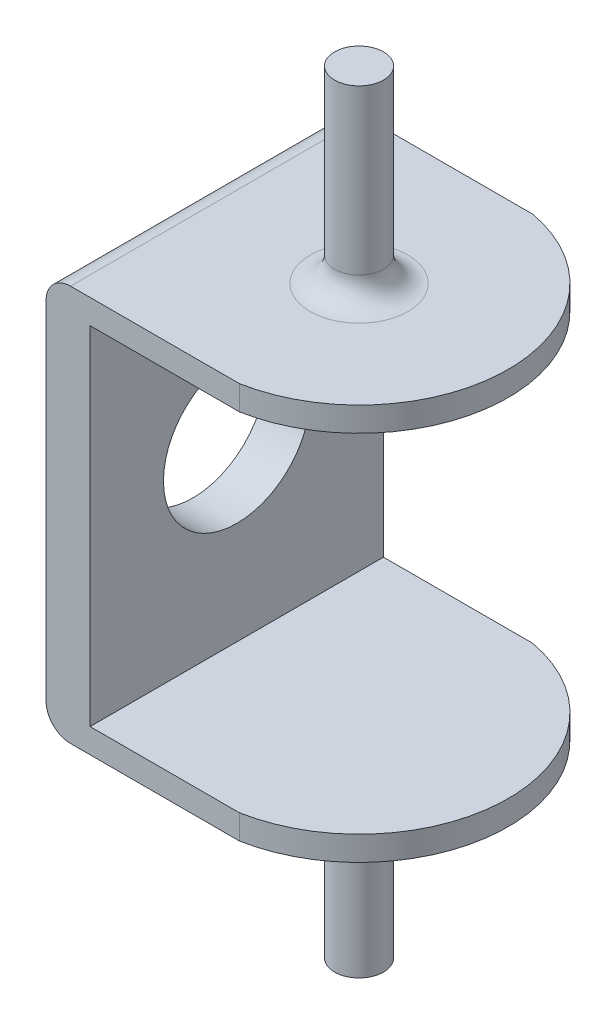
SolidWorks part; units mm, degrees
ref_plane "Front Plane" through (0, 0, 0) normal (0, 0, 1) x (1, 0, 0)
ref_plane "Top Plane" through (0, 0, 0) normal (0, 1, 0) x (1, 0, 0)
ref_plane "Right Plane" through (0, 0, 0) normal (1, 0, 0) x (0, 0, -1)
sketch "Sketch2" plane through (0, 0, 0) normal (1, 0, 0) x (0, 0, -1)
  line L0 (-230.7486, 0) -> (222.4156, 0) construction
  line L1 (0, 158.9337) -> (0, -158.9337)
  dimension "D1" = 317.8675
sweep "Sweep1" add path "Sketch2" circular profile diameter 20 parameters "D3"=20
sketch "Sketch13" plane through (0, 158.9337, 0) normal (0, 1, 0) x (1, 0, 0)
  circle A0 centre (0, 0) radius 10
  circle A1 centre (0, 0) radius 10 construction
extrude "Cut-Extrude1" cut sketch "Sketch13" against normal blind 5.9
sketch "Sketch14" plane through (0, 153.0337, 0) normal (0, 1, 0) x (1, 0, 0)
  circle A0 centre (0, 0) radius 10
extrude "Boss-Extrude1" add sketch "Sketch14" along normal blind 4
ref_plane "Plane1" through (0, -0.95, 0) normal (0, -1, 0) x (-1, 0, 0)
sketch "Sketch15" plane through (0, 0, 0) normal (0, 0, 1) x (1, 0, 0)
  line L0 (0, 157.0337) -> (0, -158.9337) construction
  line L1 (10, 157.0337) -> (-10, 157.0337) construction
  line L2 (-10, -158.9337) -> (10, -158.9337) construction
  dimension "D1" = 315.9675
ref_plane "Plane2" through (0, 80.05, 0) normal (0, -1, 0) x (-1, 0, 0)
sketch "Sketch16" plane through (0, 80.05, 0) normal (0, -1, 0) x (-1, 0, 0)
  line L0 (11.0124, 60) -> (60, 60)
  line L1 (-11.0124, 60) -> (11.0124, 60)
  line L3 (-11.0124, -60) -> (11.0124, -60)
  line L5 (-11.0124, 60) -> (11.0124, -60) construction
  line L6 (-11.0124, -60) -> (11.0124, 60) construction
  line L7 (11.0124, -60) -> (60, -60)
  line L10 (60, -60) -> (60, 60)
  line L11 (-27.9737, 0) -> (25.3941, 0) construction
  arc A0 (-11.0124, -60) -> (-11.0124, 60) centre (0, 0) cw
  point P0 (0, 0)
  point P13 (-1.2898, 0)
  dimension "D1" = 60
  dimension "D2" = 60
extrude "Boss-Extrude2" add sketch "Sketch16" along normal blind 10
mirror "Mirror1" about plane through (0, -0.95, 0) normal (0, -1, 0) of "Boss-Extrude2"
sketch "Sketch17" plane through (0, 0, -60) normal (0, 0, -1) x (-1, 0, 0)
  line L0 (60, 70.05) -> (-11.0124, 70.05) construction
  line L1 (60, -71.95) -> (50, -71.95)
  line L3 (60, 70.05) -> (50, 70.05)
  line L4 (50, -71.95) -> (50, 70.05)
  line L5 (60, -71.95) -> (50, 70.05) construction
  line L6 (60, 70.05) -> (50, -71.95) construction
  line L7 (60, -71.95) -> (-11.0124, -71.95) construction
  line L9 (60, 80.05) -> (60, 70.05)
  line L10 (60, -81.95) -> (60, -71.95)
  line L11 (60, -81.95) -> (68, -81.95)
  line L12 (68, -81.95) -> (68, 80.05)
  line L13 (68, 80.05) -> (60, 80.05)
  point P0 (55, -0.95)
  dimension "D1" = 8
extrude "Boss-Extrude3" add sketch "Sketch17" against normal up to surface (120 mm away) up to face at (-24.4938, 75.05, 60)
sketch "Sketch18" plane through (-50, 0, 0) normal (1, 0, 0) x (0, 0, -1)
  line L0 (-60, 70.05) -> (60, 70.05)
  line L1 (60, 70.05) -> (60, -71.95)
  line L2 (60, -71.95) -> (-60, -71.95)
  line L3 (-60, -71.95) -> (-60, 70.05)
extrude "Cut-Extrude2" cut sketch "Sketch18" along normal through all
sketch "Sketch19" plane through (-68, 0, 0) normal (-1, 0, 0) x (0, 0, 1)
  circle A0 centre (0, 0) radius 30
extrude "Cut-Extrude3" cut sketch "Sketch19" against normal up to surface (18 mm away) up to face at (-50, -0.95, 0)
fillet "Fillet1" radius 10 4 edges at (-68, 80.05, 0) (-68, -81.95, 0) (0, -81.95, -10) (0, 80.05, 10)
